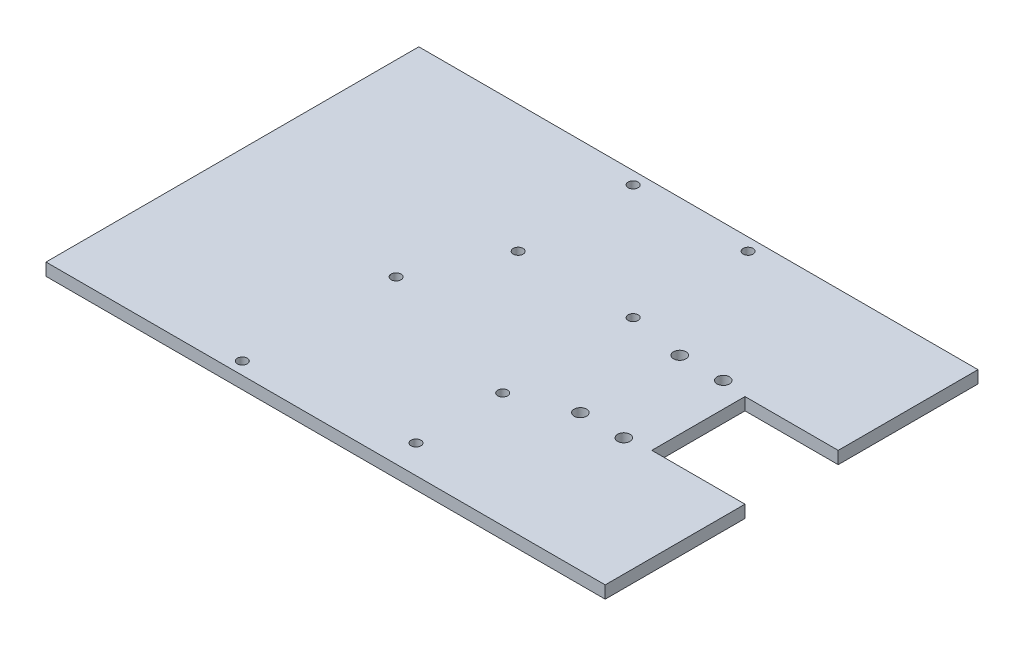
SolidWorks part; units mm, degrees
ref_plane "前视基准面" through (0, 0, 0) normal (0, 0, 1) x (1, 0, 0)
ref_plane "上视基准面" through (0, 0, 0) normal (0, 1, 0) x (1, 0, 0)
ref_plane "右视基准面" through (0, 0, 0) normal (1, 0, 0) x (0, 0, -1)
other "Configuration Table"
sketch "草图1" plane through (0, 0, 0) normal (0, 1, 0) x (1, 0, 0)
  line L1 (-90, -60) -> (90, -60)
  line L2 (-90, -60) -> (-90, 60)
  line L3 (-90, 60) -> (90, 60)
  line L4 (90, -60) -> (90, 60)
  line L5 (-90, -60) -> (90, 60) construction
  line L6 (-90, 60) -> (90, -60) construction
  point P0 (0, 0)
  dimension "D1" = 120
  dimension "D2" = 180
extrude "凸台-拉伸1" add sketch "草图1" along normal blind 4
sketch "草图2" plane through (0, 4, 0) normal (0, 1, 0) x (1, 0, 0)
  line L0 (90, -60) -> (90, 60) construction
  line L1 (66, -25) -> (85, -25) construction
  line L2 (66, -25) -> (66, 25) construction
  line L3 (66, 25) -> (85, 25) construction
  line L4 (85, -25) -> (85, 25) construction
  line L5 (66, -25) -> (85, 25) construction
  line L6 (66, 25) -> (85, -25) construction
  circle A0 centre (66, 25) radius 1.6
  circle A1 centre (66, -25) radius 1.6
  circle A2 centre (85, -25) radius 1.6
  circle A3 centre (85, 25) radius 1.6
  circle A7 centre (80.7, 7) radius 3
  point P0 (75.5, 0)
  dimension "D4" = 3.2
  dimension "D5" = 4.3
  dimension "D7" = 6
  dimension "D1" = 19
  dimension "D2" = 50
  dimension "D3" = 5
  dimension "D6" = 18
sketch "草图3" plane through (0, 4, 0) normal (0, 1, 0) x (1, 0, 0)
  line L0 (90, -60) -> (90, 60) construction
  line L1 (60, -15) -> (100, -15)
  line L2 (60, -15) -> (60, 15)
  line L3 (60, 15) -> (100, 15)
  line L4 (100, -15) -> (100, 15)
  line L5 (60, -15) -> (100, 15) construction
  line L6 (60, 15) -> (100, -15) construction
  point P0 (80, 0)
  dimension "D1" = 40
  dimension "D2" = 30
  dimension "D3" = 10
extrude "切除-拉伸2" cut sketch "草图3" against normal blind 4
sketch "草图4" plane through (0, 4, 0) normal (0, 1, 0) x (1, 0, 0)
  line L0 (90, 60) -> (-90, 60) construction
  line L1 (-17, 56) -> (20, 56) construction
  line L2 (-17, 56) -> (-17, 19) construction
  line L3 (-17, 19) -> (20, 19) construction
  line L4 (20, 56) -> (20, 19) construction
  line L6 (60, 15) -> (60, -15) construction
  circle A0 centre (-17, 56) radius 1.6
  circle A1 centre (20, 56) radius 1.6
  circle A2 centre (20, 19) radius 1.6
  circle A3 centre (-17, 19) radius 1.6
  dimension "D4" = 3.2
  dimension "D1" = 37
  dimension "D2" = 4
  dimension "D3" = 40
extrude "切除-拉伸3" cut sketch "草图4" against normal blind 4
sketch "草图5" plane through (0, 4, 0) normal (0, 1, 0) x (1, 0, 0)
  line L0 (-90, -60) -> (90, -60) construction
  line L1 (-30.8, -56) -> (20, -56) construction
  line L2 (-30.8, -56) -> (-30.8, -7.8) construction
  line L3 (-30.8, -7.8) -> (20, -7.8) construction
  line L4 (20, -56) -> (20, -7.8) construction
  line L8 (60, 15) -> (60, -15) construction
  circle A0 centre (-29.5, -7.8) radius 1.6
  circle A1 centre (20, -23) radius 1.6
  circle A2 centre (20, -50.9) radius 1.6
  circle A3 centre (-30.8, -56) radius 1.6
  dimension "D8" = 3.2
  dimension "D1" = 48.2
  dimension "D2" = 50.8
  dimension "D3" = 4
  dimension "D4" = 40
  dimension "D5" = 1.3
  dimension "D6" = 15.2
  dimension "D7" = 27.9
extrude "切除-拉伸4" cut sketch "草图5" against normal blind 4
sketch "草图7" plane through (0, 0, 0) normal (0, -1, 0) x (1, 0, 0)
  line L0 (0, 0) -> (130.1672, 0) construction
  line L1 (60, -15) -> (60, 15) construction
  circle A0 centre (52, 16) radius 2
  circle A1 centre (38, 16) radius 2
  circle A2 centre (52, -16) radius 2
  circle A3 centre (38, -16) radius 2
  dimension "D2" = 4
  dimension "D5" = 4
  dimension "D1" = 8
  dimension "D3" = 16
  dimension "D4" = 0
  dimension "D6" = 14
  dimension "D7" = 16
extrude "切除-拉伸5" cut sketch "草图7" against normal blind 10
